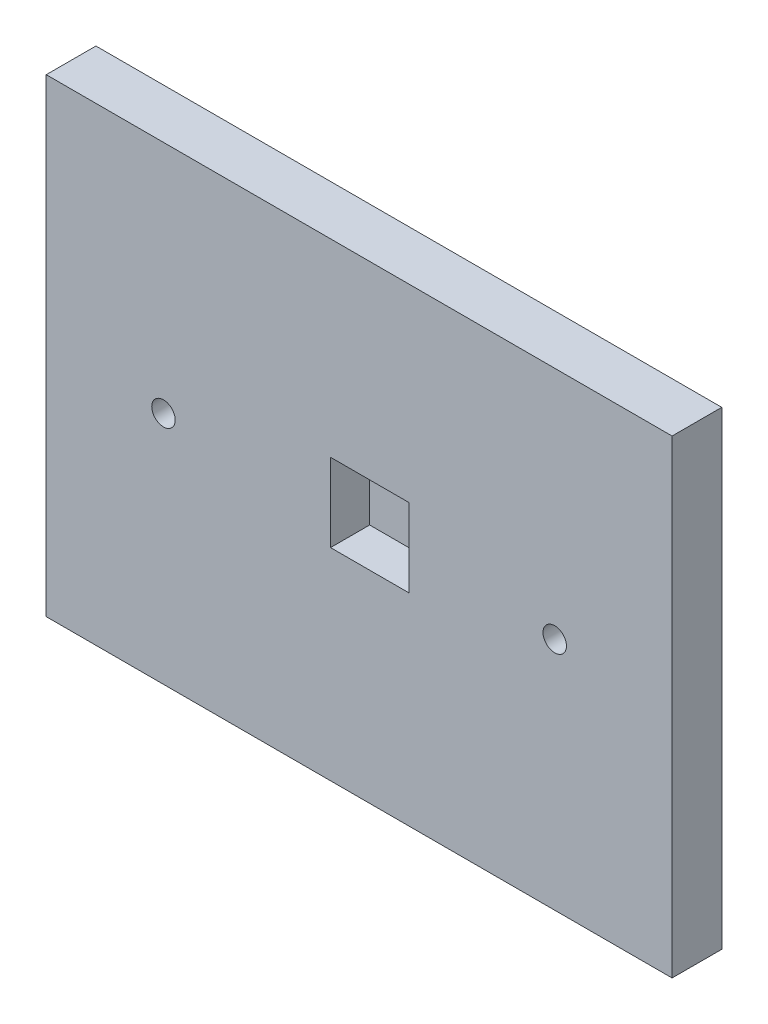
SolidWorks part; units mm, degrees
ref_plane "Front Plane" through (0, 0, 0) normal (0, 0, 1) x (1, 0, 0)
ref_plane "Top Plane" through (0, 0, 0) normal (0, 1, 0) x (1, 0, 0)
ref_plane "Right Plane" through (0, 0, 0) normal (1, 0, 0) x (0, 0, -1)
sketch "Sketch1" plane through (0, 0, 0) normal (0, 0, 1) x (1, 0, 0)
  line L1 (-32.4571, 46.2857) -> (127.5429, 46.2857)
  line L2 (-32.4571, 46.2857) -> (-32.4571, -73.7143)
  line L3 (-32.4571, -73.7143) -> (127.5429, -73.7143)
  line L4 (127.5429, 46.2857) -> (127.5429, -73.7143)
  circle A0 centre (97.5422, -13.7143) radius 3
  circle A1 centre (-2.4859, -13.7143) radius 3
  dimension "D3" = 6
  dimension "D1" = 120
  dimension "D2" = 159.9999
extrude "Boss-Extrude1" add sketch "Sketch1" along normal blind 12.7
sketch "Sketch3" plane through (0, 0, 12.7) normal (0, 0, 1) x (1, 0, 0)
  line L1 (40.2204, -2.0791) -> (60.2204, -2.0791)
  line L2 (40.2204, -2.0791) -> (40.2204, -22.0791)
  line L3 (40.2204, -22.0791) -> (60.2204, -22.0791)
  line L4 (60.2204, -2.0791) -> (60.2204, -22.0791)
  line L5 (40.2204, -2.0791) -> (60.2204, -22.0791) construction
  line L6 (40.2204, -22.0791) -> (60.2204, -2.0791) construction
  point P0 (50.2204, -12.0791)
  dimension "D1" = 20
  dimension "D2" = 20
extrude "Cut-Extrude3" cut sketch "Sketch3" against normal blind 10
